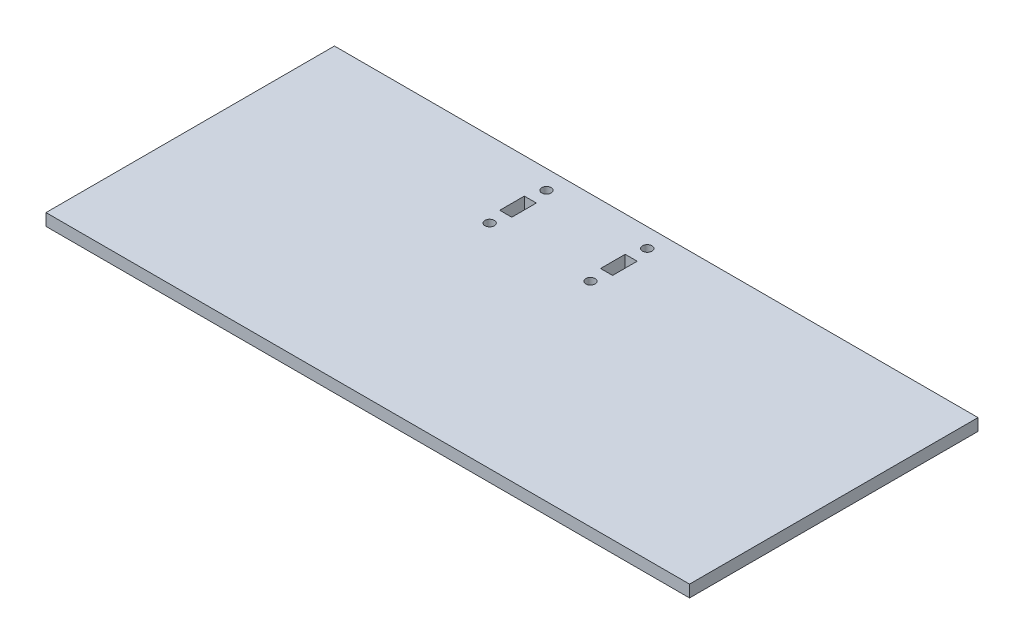
SolidWorks part; units mm, degrees
ref_plane "Front Plane" through (0, 0, 0) normal (0, 0, 1) x (1, 0, 0)
ref_plane "Top Plane" through (0, 0, 0) normal (0, 1, 0) x (1, 0, 0)
ref_plane "Right Plane" through (0, 0, 0) normal (1, 0, 0) x (0, 0, -1)
sketch "Sketch1" plane through (0, 0, 0) normal (0, 1, 0) x (1, 0, 0)
  line L0 (148.63, 152.4) -> (148.63, 0) construction
  line L1 (0, 0) -> (340, 0)
  line L2 (0, 0) -> (0, 152.4)
  line L3 (0, 152.4) -> (340, 152.4)
  line L4 (340, 0) -> (340, 152.4)
  line L5 (118.825, 133.9) -> (125.175, 133.9)
  line L6 (118.825, 133.9) -> (118.825, 120.9)
  line L7 (118.825, 120.9) -> (125.175, 120.9)
  line L8 (125.175, 133.9) -> (125.175, 120.9)
  line L9 (172.085, 133.9) -> (178.435, 133.9)
  line L10 (172.085, 133.9) -> (172.085, 120.9)
  line L11 (172.085, 120.9) -> (178.435, 120.9)
  line L12 (178.435, 133.9) -> (178.435, 120.9)
  line L13 (122, 152.4) -> (122, 0) construction
  line L14 (175.26, 152.4) -> (175.26, 0) construction
  line L15 (122, 142.4) -> (175.26, 142.4) construction
  line L16 (122, 112.4) -> (175.26, 112.4) construction
  line L17 (118.825, 127.4) -> (178.435, 127.4) construction
  circle A0 centre (122, 142.4) radius 2.4892
  circle A1 centre (175.26, 142.4) radius 2.4892
  circle A2 centre (122, 112.4) radius 2.4892
  circle A3 centre (175.26, 112.4) radius 2.4892
  point P27 (148.63, 142.4)
  point P28 (148.63, 112.4)
  point P31 (148.63, 127.4)
  point P32 (122, 120.9)
  dimension "D6" = 4.9784
  dimension "D1" = 340
  dimension "D2" = 152.4
  dimension "D3" = 13
  dimension "D4" = 6.35
  dimension "D5" = 30
  dimension "D7" = 15
  dimension "D8" = 164.74
  dimension "D9" = 122
  dimension "D10" = 10
extrude "Boss-Extrude1" add sketch "Sketch1" along normal blind 6.35
